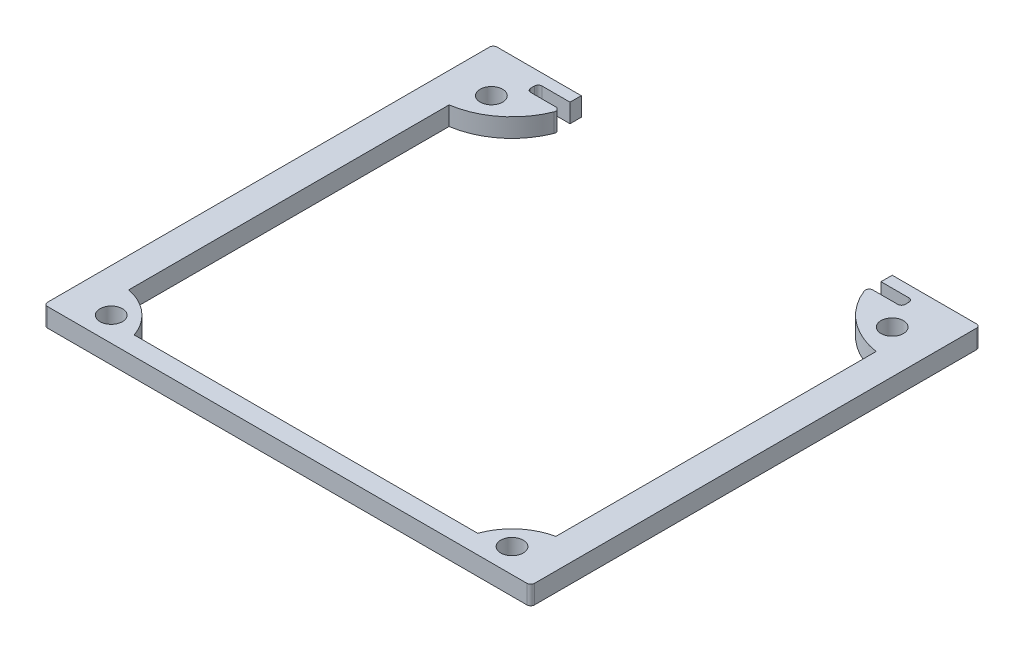
SolidWorks part; units mm, degrees
ref_plane "Front Plane" through (0, 0, 0) normal (0, 0, 1) x (1, 0, 0)
ref_plane "Top Plane" through (0, 0, 0) normal (0, 1, 0) x (1, 0, 0)
ref_plane "Right Plane" through (0, 0, 0) normal (1, 0, 0) x (0, 0, -1)
sketch "Sketch1" plane through (0, 0, 0) normal (0, 1, 0) x (1, 0, 0)
  line L0 (6.5, 0) -> (6.5, 6.5) construction
  line L1 (0, 0) -> (120, 0) construction
  line L3 (0, 120) -> (120, 120) construction
  line L5 (113.5, 0) -> (113.5, 6.5) construction
  line L6 (6.5, 120) -> (6.5, 108) construction
  line L7 (113.5, 120) -> (113.5, 108) construction
  line L8 (-5, 120) -> (-5, 0)
  line L9 (125, 120) -> (125, 0)
  line L10 (-5, 0) -> (125, 0)
  line L14 (125, 120) -> (-5, 120)
  line L16 (0, 100) -> (0, 15)
  line L17 (120, 100) -> (120, 15)
  line L19 (20, 115) -> (19.3649, 115)
  line L21 (100, 115) -> (100.6351, 115)
  line L22 (20, 115) -> (100, 115)
  line L25 (15, 5) -> (14.1421, 5)
  line L26 (105, 5) -> (105.8579, 5)
  line L27 (15, 5) -> (105, 5)
  circle A0 centre (6.5, 6.5) radius 3
  circle A1 centre (113.5, 6.5) radius 3
  arc A2 (14.1421, 5) -> (0, 15) centre (0, 0) ccw
  arc A3 (105.8579, 5) -> (120, 15) centre (120, 0) cw
  circle A4 centre (6.5, 108) radius 3
  circle A5 centre (113.5, 108) radius 3
  arc A6 (19.3649, 115) -> (0, 100) centre (0, 120) cw
  arc A7 (100.6351, 115) -> (120, 100) centre (120, 120) ccw
  dimension "D7" = 6
  dimension "D8" = 6
  dimension "D9" = 15
  dimension "D10" = 15
  dimension "D13" = 6
  dimension "D16" = 6
  dimension "D17" = 20
  dimension "D18" = 20
  dimension "D20" = 11.5
  dimension "D2" = 120
  dimension "D3" = 6.5
  dimension "D4" = 5
  dimension "D5" = 6.5
  dimension "D6" = 85
  dimension "D11" = 85
  dimension "D12" = 12
  dimension "D14" = 80
  dimension "D15" = 12
  dimension "D19" = 90
  dimension "D21" = 11.5
  dimension "D22" = 5
  dimension "D23" = 11.5
extrude "Boss-Extrude1" add sketch "Sketch1" along normal blind 5
sketch "Sketch2" plane through (0, 5, 0) normal (0, 1, 0) x (1, 0, 0)
  line L0 (125, 120) -> (-5, 120) construction
  line L1 (10, 114) -> (110, 114)
  line L2 (10, 114) -> (10, 117)
  line L3 (10, 117) -> (110, 117)
  line L4 (110, 114) -> (110, 117)
  point P8 (60, 120)
  point P9 (60, 117)
  dimension "D1" = 3
  dimension "D2" = 6
  dimension "D3" = 0
  dimension "D4" = 100
extrude "Cut-Extrude1" cut sketch "Sketch2" against normal blind 10
fillet "Fillet1" radius 1 4 edges at (10, 2.5, -117) (110, 2.5, -117) (110, 2.5, -114) (10, 2.5, -114)
fillet "Fillet2" radius 1 1 edges at (19.0788, 2.5, -114)
fillet "Fillet3" radius 1 1 edges at (100.9212, 2.5, -114)
sketch "Sketch3" plane through (0, 5, 0) normal (0, 1, 0) x (1, 0, 0)
  line L0 (18.4907, 113.562) -> (18.4907, 120)
  line L1 (125, 120) -> (-5, 120) construction
  line L2 (101.5093, 113.562) -> (101.5093, 120)
  line L3 (101.5093, 120) -> (18.4907, 120)
  line L4 (18.4907, 113.562) -> (101.5093, 113.562)
  arc A0 (18.5932, 112.6316) -> (17.6635, 114) centre (17.6635, 113) ccw construction
  arc A1 (102.3365, 114) -> (101.4068, 112.6316) centre (102.3365, 113) ccw construction
extrude "Cut-Extrude2" cut sketch "Sketch3" against normal blind 10
sketch "Sketch4" plane through (0, 5, 0) normal (0, 1, 0) x (1, 0, 0)
  line L0 (120, 57.5) -> (117, 57.5) construction
  line L1 (120, 15) -> (120, 100) construction
  line L2 (120, 100) -> (120, 120) construction
  line L3 (117, 103.5675) -> (120, 103.5675)
  line L4 (117, 103.5675) -> (117, 11.5594)
  line L5 (117, 11.5594) -> (120, 11.5594)
  line L6 (120, 11.5594) -> (120, 103.5675)
  line L7 (2.9798, 57.5) -> (-0.0202, 57.5) construction
  line L8 (2.9798, 100) -> (2.9798, 120) construction
  line L9 (-0.0202, 103.5675) -> (2.9798, 103.5675)
  line L10 (-0.0202, 103.5675) -> (-0.0202, 11.5594)
  line L11 (-0.0202, 11.5594) -> (2.9798, 11.5594)
  line L12 (2.9798, 11.5594) -> (2.9798, 103.5675)
  dimension "D1" = 3
  dimension "D2" = 3
extrude "Boss-Extrude2" add sketch "Sketch4" against normal blind 5 contours L4 L5 L6 L3 | L12 L9 L10 L11
fillet "Fillet4" radius 1 4 edges at (125, 2.5, -120) (125, 2.5, 0) (-5, 2.5, -120) (-5, 2.5, 0)
